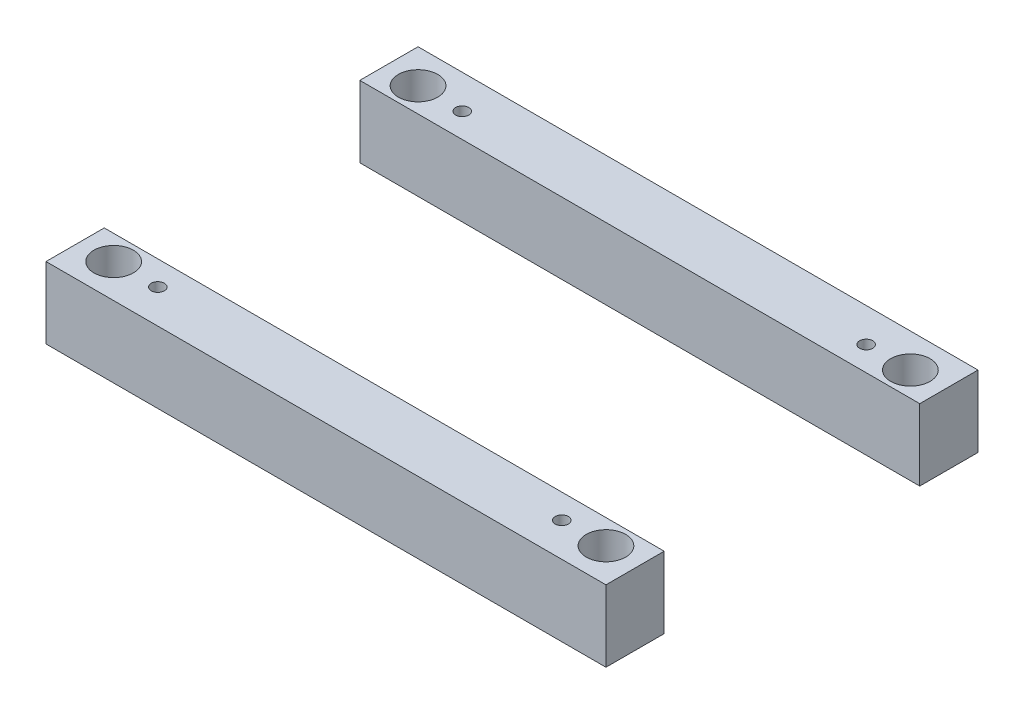
SolidWorks part; units mm, degrees
material "1.2312 (40CrMnMoS8-6)"
ref_plane "Płaszczyzna przednia" through (0, 0, 0) normal (0, 0, 1) x (1, 0, 0)
ref_plane "Płaszczyzna górna" through (0, 0, 0) normal (0, 1, 0) x (1, 0, 0)
ref_plane "Płaszczyzna prawa" through (0, 0, 0) normal (1, 0, 0) x (0, 0, -1)
sketch "Szkic1" plane through (0, 0, 0) normal (0, 1, 0) x (1, 0, 0)
  line L0 (298, 396) -> (298, 0) construction
  line L1 (0, 0) -> (596, 0)
  line L2 (0, 0) -> (0, 396)
  line L3 (0, 396) -> (596, 396)
  line L4 (596, 0) -> (596, 396)
  line L5 (0, 198) -> (596, 198) construction
  circle A0 centre (36, 360) radius 21
  circle A1 centre (36, 360) radius 24
  circle A2 centre (560, 360) radius 24
  circle A3 centre (560, 360) radius 21
  circle A4 centre (560, 36) radius 21
  circle A5 centre (560, 36) radius 24
  circle A6 centre (36, 36) radius 24
  circle A7 centre (36, 36) radius 21
  dimension "D3" = 48
  dimension "D4" = 42
  dimension "D1" = 396
  dimension "D2" = 596
  dimension "D5" = 524
  dimension "D6" = 324
extrude "Dodanie-wyciągnięcie1" add sketch "Szkic1" against normal blind 76 contours A6 A7 | L1 L4 L3 L2 A2 A1 A5 A6 | A5 A4 | A2 A3 | A1 A0
sketch "Szkic3" plane through (0, 0, 0) normal (0, 1, 0) x (1, 0, 0)
  line L0 (0, 0) -> (596, 0) construction
  line L1 (83, 360) -> (513, 360)
  line L2 (83, 360) -> (83, 36)
  line L3 (83, 36) -> (513, 36)
  line L4 (513, 360) -> (513, 36)
  line L6 (298, 396) -> (298, 0) construction
  line L7 (0, 396) -> (596, 396) construction
  dimension "D4" = 215
  dimension "D1" = 430
  dimension "D2" = 324
  dimension "D3" = 36
hole_wizard "Otwór gwintowany M161" positions "Szkic 3D1" profile "Szkic2" tap size "M16" standard "ISO" end condition through all
sketch3d "Szkic 3D1"
  point P0 (83, 0, -360)
  point P2 (513, 0, -360)
  point P4 (83, 0, -36)
  point P6 (513, 0, -36)
cosmetic thread "Gwint otworu1" parameters "D2"=16
cosmetic thread "Gwint otworu2" parameters "D2"=16
cosmetic thread "Gwint otworu3" parameters "D2"=16
cosmetic thread "Gwint otworu4" parameters "D2"=16
sketch "Szkic2" plane through (83, 0, -360) normal (1, 0, 0) x (0, 0, 1)
  line L0 (0, 0) -> (0, 76)
  line L1 (0, 76) -> (7, 76)
  line L2 (7, 76) -> (7, 0)
  line L5 (7, 0) -> (0, 0)
  line L11 (0, -6.35) -> (0, 107.95) construction
  dimension "Średnica otworu gwintowanego na wylot" = 14
  dimension "Głębokość otworu gwintowanego na wylot" = 76
sketch "Szkic4" plane through (0, 0, 0) normal (0, 1, 0) x (1, 0, 0)
  line L0 (0, 198) -> (596, 198) construction
  line L1 (0, 0) -> (0, 396) construction
  line L2 (596, 0) -> (596, 396) construction
  line L3 (-37.3184, 62) -> (-37.3184, 334)
  line L4 (-37.3184, 334) -> (631.5316, 334)
  line L5 (631.5316, 334) -> (631.5316, 62)
  line L6 (-37.3184, 62) -> (631.5316, 62)
  point P11 (631.5316, 198)
  point P12 (-37.3184, 198)
extrude "Wytnij-wyciągnięcie1" cut sketch "Szkic4" against normal blind 108
